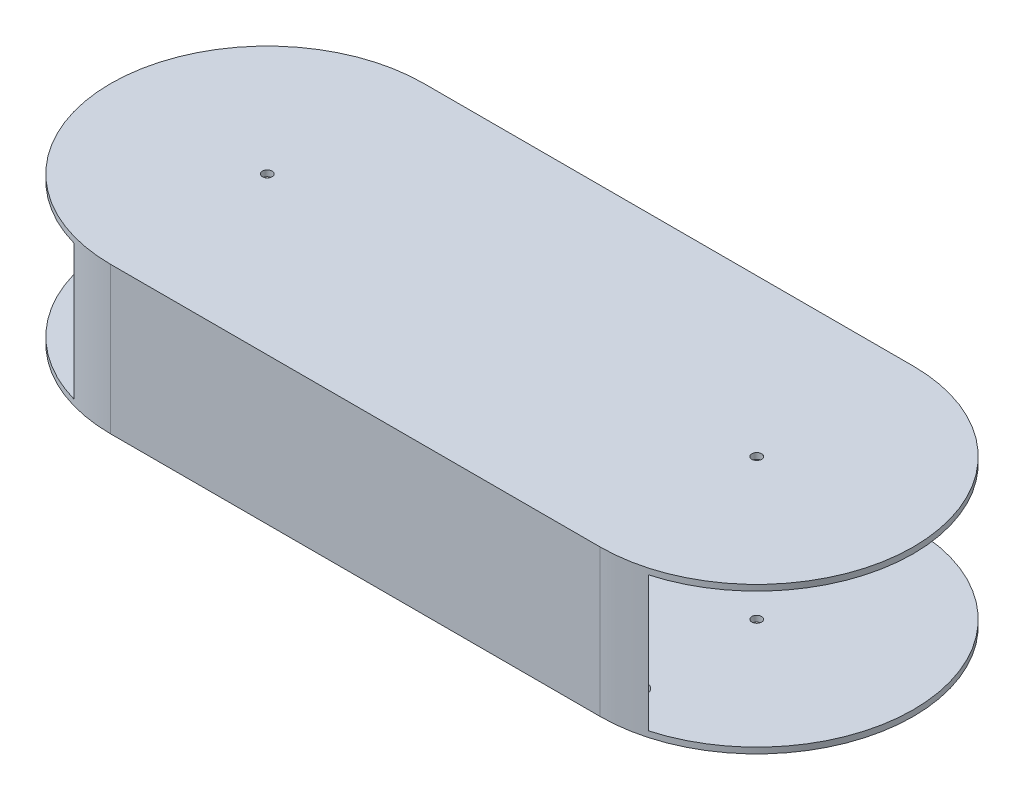
SolidWorks part; units mm, degrees
ref_plane "前视基准面" through (0, 0, 0) normal (0, 0, 1) x (1, 0, 0)
ref_plane "上视基准面" through (0, 0, 0) normal (0, 1, 0) x (1, 0, 0)
ref_plane "右视基准面" through (0, 0, 0) normal (1, 0, 0) x (0, 0, -1)
other "Configuration Table"
sketch "草图1" plane through (0, 0, 0) normal (0, 1, 0) x (1, 0, 0)
  line L0 (0, 0) -> (250, 0) construction
  line L1 (0, 80) -> (250, 80)
  line L2 (0, -80) -> (250, -80)
  arc A0 (0, 80) -> (0, -80) centre (0, 0) ccw
  arc A1 (250, -80) -> (250, 80) centre (250, 0) ccw
  point P3 (125, 0)
  dimension "D2" = 80
  dimension "D1" = 250
extrude "凸台-拉伸1" add sketch "草图1" along normal blind 75
ref_plane "基准面2" through (0, 72, 0) normal (0, 1, 0) x (1, 0, 0)
sketch "草图3" plane through (0, 72, 0) normal (0, 1, 0) x (1, 0, 0)
  line L0 (-80, 0) -> (339.3371, 0) construction
  line L1 (0, 80) -> (0, -80) construction
  line L2 (0, 0) -> (250, 0) construction
  line L5 (0, 77) -> (250, 77)
  line L6 (0, -77) -> (250, -77)
  arc A4 (0, 80) -> (0, -80) centre (0, 0) ccw construction
  arc A5 (0, 77) -> (0, -77) centre (0, 0) ccw
  arc A6 (250, -77) -> (250, 77) centre (250, 0) ccw
  point P7 (125, 0)
  dimension "D2" = 77
  dimension "D1" = 250
extrude "切除-拉伸1" cut sketch "草图3" against normal blind 69
ref_plane "基准面3" through (0, 0, -80) normal (0, 0, -1) x (-1, 0, 0)
sketch "草图4" plane through (0, 0, -80) normal (0, 0, -1) x (-1, 0, 0)
  line L0 (0, 83.3256) -> (0, -18.0969) construction
  line L1 (80, 37.5) -> (-145.5402, 37.5) construction
  line L2 (80, 0) -> (80, 75) construction
  line L3 (80, 75) -> (0, 75) construction
  line L4 (-80, 72) -> (80, 72)
  line L5 (-80, 72) -> (-80, 3)
  line L6 (-80, 3) -> (80, 3)
  line L7 (80, 72) -> (80, 3)
  line L8 (-125, 126.5971) -> (-125, 29.4783) construction
  line L10 (-330, 75) -> (-330, 0) construction
  line L11 (-330, 72) -> (-330, 3)
  line L12 (-170, 3) -> (-330, 3)
  line L13 (-170, 72) -> (-170, 3)
  line L14 (-170, 72) -> (-330, 72)
  dimension "D1" = 3
  dimension "D2" = 160
  dimension "D3" = 69
  dimension "D4" = 205
extrude "切除-拉伸2" cut sketch "草图4" against normal blind 157
sketch "草图5" plane through (0, 3, 0) normal (0, 1, 0) x (1, 0, 0)
  circle A0 centre (0, 0) radius 2.5
  dimension "D1" = 5
extrude "切除-拉伸3" cut sketch "草图5" against normal through all
sketch "草图6" plane through (0, 72, 0) normal (0, 1, 0) x (1, 0, 0)
  circle A0 centre (0, 0) radius 2.5
  dimension "D1" = 5
extrude "切除-拉伸16" cut sketch "草图6" along normal up to next
ref_plane "基准面4" through (0, 75, 0) normal (0, 1, 0) x (1, 0, 0)
ref_plane "基准面5" through (0, 0, 0) normal (0, -1, 0) x (-1, 0, 0)
sketch "草图8" plane through (0, 0, 0) normal (0, -1, 0) x (-1, 0, 0)
  line L0 (0, -8.262) -> (0, 44.855) construction
  circle A0 centre (0, -61.25) radius 5
  dimension "D1" = 10
  dimension "D2" = 61.25
extrude "切除-拉伸18" cut sketch "草图8" against normal up to next
cosmetic thread "装饰螺纹线4" parameters "D2"=11
sketch "草图9" plane through (0, 0, 0) normal (0, -1, 0) x (1, 0, 0)
  line L0 (0, -0.8123) -> (0, -72.6392) construction
  circle A0 centre (0, -61.25) radius 5
  dimension "D1" = 10
  dimension "D2" = 61.25
extrude "切除-拉伸19" cut sketch "草图9" against normal up to next
cosmetic thread "装饰螺纹线3" parameters "D2"=11
sketch "草图10" plane through (0, 75, 0) normal (0, 1, 0) x (1, 0, 0)
  line L0 (0, 0) -> (330, 0) construction
  line L1 (250, -80) -> (250, 80) construction
  line L2 (41.25, 80) -> (-41.25, 80) construction
  arc A0 (250, -80) -> (250, 80) centre (250, 0) ccw construction
  circle A1 centre (250, 0) radius 2.5
  dimension "D1" = 5
extrude "切除-拉伸20" cut sketch "草图10" against normal through all both and the other way through all contours A1
sketch "草图11" plane through (0, 0, 0) normal (0, -1, 0) x (1, 0, 0)
  line L0 (250.0413, -4.5419) -> (250.0413, 75.4581) construction
  line L1 (0, 0) -> (316.3597, 0) construction
  line L2 (0, 61.25) -> (250, 61.25) construction
  line L3 (0, -61.25) -> (250.0413, -61.25)
  circle A0 centre (250, 61.25) radius 5
  circle A1 centre (250.0413, -61.25) radius 5
  dimension "D2" = 10
  dimension "D3" = 10
  dimension "D1" = 250
extrude "切除-拉伸21" cut sketch "草图11" against normal up to next and the other way through all
cosmetic thread "装饰螺纹线5" parameters "D2"=11
cosmetic thread "装饰螺纹线6" parameters "D2"=11
sketch "草图12" plane through (0, 72, 0) normal (0, 1, 0) x (1, 0, 0)
  line L0 (79.2765, 78.0424) -> (79.2765, -53.3717) construction
  line L1 (168.2619, 78.0424) -> (168.2619, -37.0405) construction
  line L2 (84.7326, 80) -> (116.1117, -2.3324)
  line L3 (41.25, 80) -> (-41.25, 80) construction
  line L4 (0, -80) -> (250, -80) construction
  line L5 (95.9613, 80) -> (121.5623, 12.828)
  line L6 (159.5327, 80) -> (128.8656, -6.3343)
  line L7 (145.7129, 80) -> (121.5623, 12.828)
  line L8 (88.1876, -80) -> (102.6985, -80)
  line L9 (145.7129, 80) -> (159.5327, 80)
  line L10 (84.7326, 80) -> (95.9613, 80)
  line L11 (145.7129, -80) -> (156.9415, -80)
  line L12 (116.1117, -2.3324) -> (88.1876, -80)
  line L13 (128.8656, -6.3343) -> (156.9415, -80)
  line L14 (123.4488, -21.5836) -> (145.7129, -80)
  line L15 (123.4488, -21.5836) -> (102.6985, -80)
extrude "凸台-拉伸2" add sketch "草图12" against normal up to surface (69 mm away) up to face at (250.0413, 3, -56.25)
